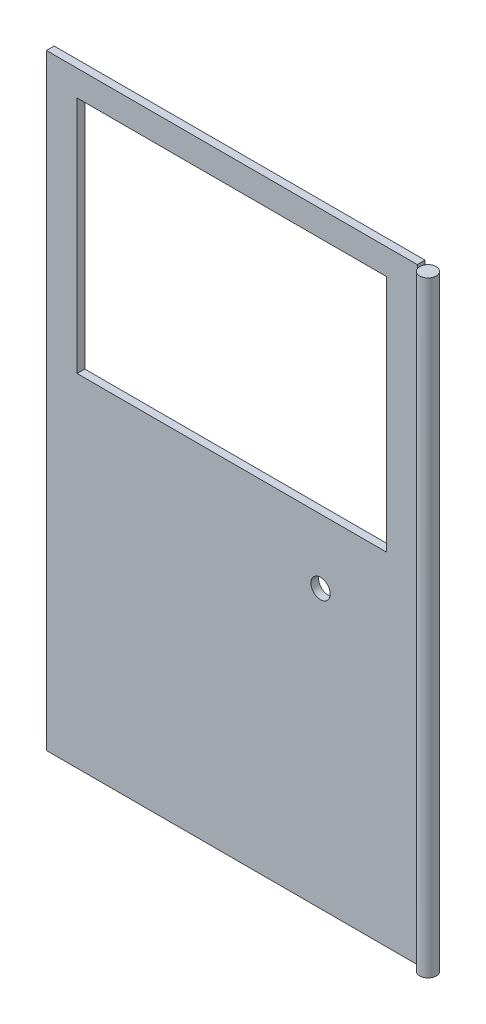
SolidWorks part; units mm, degrees
ref_plane "Front Plane" through (0, 0, 0) normal (0, 0, 1) x (1, 0, 0)
ref_plane "Top Plane" through (0, 0, 0) normal (0, 1, 0) x (1, 0, 0)
ref_plane "Right Plane" through (0, 0, 0) normal (1, 0, 0) x (0, 0, -1)
sketch "Sketch1" plane through (0, 0, 0) normal (0, 0, 1) x (1, 0, 0)
  line L0 (0, 0) -> (0, 245) construction
  line L1 (-287.5, 470) -> (287.5, 470)
  line L2 (-287.5, 470) -> (-287.5, -470)
  line L3 (-287.5, -470) -> (287.5, -470)
  line L4 (287.5, 470) -> (287.5, -470)
  line L5 (-287.5, 470) -> (287.5, -470) construction
  line L6 (-287.5, -470) -> (287.5, 470) construction
  line L7 (240, 60) -> (-240, 60)
  line L8 (240, 60) -> (240, 430)
  line L9 (240, 430) -> (-240, 430)
  line L10 (-240, 60) -> (-240, 430)
  line L11 (240, 60) -> (-240, 430) construction
  line L12 (240, 430) -> (-240, 60) construction
  point P0 (0, 0)
  point P6 (0, 245)
  dimension "D1" = 575
  dimension "D2" = 940
  dimension "D3" = 530
  dimension "D4" = 370
  dimension "D5" = 480
extrude "Boss-Extrude1" add sketch "Sketch1" along normal blind 12
sketch "Sketch2" plane through (0, 0, 0) normal (0, 1, 0) x (1, 0, 0)
  line L0 (287.5, 0) -> (317.5, 0) construction
  line L1 (304.8, -12.7) -> (317.5, -12.7) construction
  line L2 (317.5, 0) -> (317.5, -12.7) construction
  circle A0 centre (304.8, -12.7) radius 12.7
  dimension "D1" = 25.4
  dimension "D2" = 30
extrude "Boss-Extrude2" add sketch "Sketch2" along normal up to surface and the other way up to surface separate body up to face at (0, 470, 6) other way up to face at (0, -470, 6)
sketch "Sketch3" plane through (0, 0, 0) normal (0, 0, -1) x (-1, 0, 0)
  line L0 (-232.5, -40) -> (-287.5, -40) construction
  line L1 (-287.5, -470) -> (-287.5, 470) construction
  line L2 (-232.5, -40) -> (-232.5, 60) construction
  line L3 (240, 60) -> (-240, 60) construction
  line L4 (-232.5, -40) -> (-137.5, -40) construction
  line L5 (-137.5, -40) -> (-125, -40) construction
  line L6 (-245, -40) -> (-232.5, -40) construction
  circle A0 centre (-232.5, -40) radius 12.5 construction
  circle A1 centre (-137.5, -40) radius 12.5 construction
  circle A2 centre (-137.5, -40) radius 15
  dimension "D2" = 25
  dimension "D5" = 30
  dimension "D1" = 55
  dimension "D3" = 100
  dimension "D4" = 120
extrude "Cut-Extrude1" cut sketch "Sketch3" against normal through all contours A1 | A2
